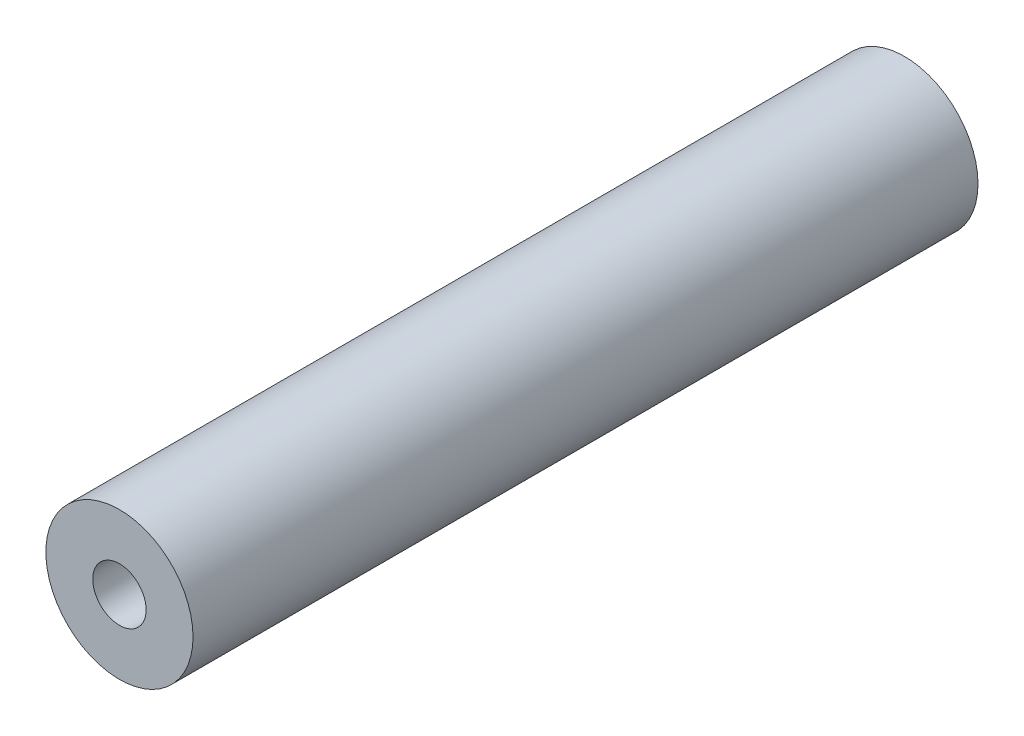
SolidWorks part; units mm, degrees
material "Alloy Steel"
ref_plane "Front Plane" through (0, 0, 0) normal (0, 0, 1) x (1, 0, 0)
ref_plane "Top Plane" through (0, 0, 0) normal (0, 1, 0) x (1, 0, 0)
ref_plane "Right Plane" through (0, 0, 0) normal (1, 0, 0) x (0, 0, -1)
sketch "Sketch1" plane through (0, 0, 0) normal (0, 0, 1) x (1, 0, 0)
  circle A0 centre (0, 0) radius 4.7625
  dimension "D1" = 9.525
extrude "Boss-Extrude1" add sketch "Sketch1" along normal mid plane 50.8
hole_wizard "Tap Drill for #8-32 Tap1" positions "3DSketch1" profile "Sketch2" hole size "#8-32" standard "ANSI Inch"
sketch3d "3DSketch1"
  line L0 (0, 0, 25.4) -> (0, 0, -25.4) construction
  point P0 (0, 0, 25.4)
  point P4 (0, 0, -25.4)
sketch "Sketch2" plane through (0, 0, 25.4) normal (1, 0, 0) x (0, -1, 0)
  line L0 (0, 0) -> (0, 7.3878)
  line L1 (0, 7.3878) -> (1.7272, 6.35)
  line L2 (1.7272, 6.35) -> (1.7272, 0)
  line L5 (1.7272, 0) -> (0, 0)
  line L10 (0, 7.3878) -> (-1.7272, 6.35) construction
  line L11 (0, -6.35) -> (0, 107.95) construction
  dimension "Hole Dia." = 3.4544
  dimension "Hole Depth" = 6.35
  dimension "Drill Angle" = 118
